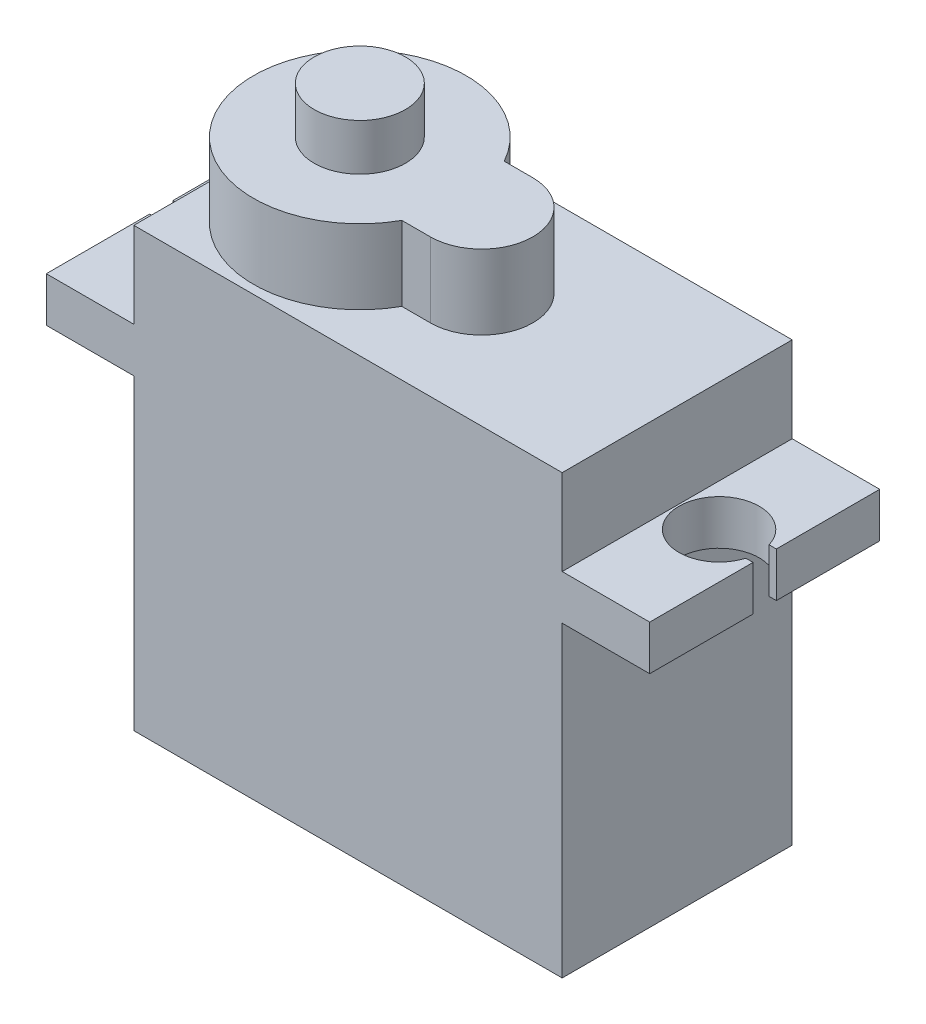
SolidWorks part; units mm, degrees
ref_plane "Front Plane" through (0, 0, 0) normal (0, 0, 1) x (1, 0, 0)
ref_plane "Top Plane" through (0, 0, 0) normal (0, 1, 0) x (1, 0, 0)
ref_plane "Right Plane" through (0, 0, 0) normal (1, 0, 0) x (0, 0, -1)
sketch "Sketch1" plane through (0, 0, 0) normal (0, 0, 1) x (1, 0, 0)
  line L0 (0, 0) -> (23, 0)
  line L1 (23, 0) -> (23, 16.5)
  line L2 (23, 16.5) -> (27.7, 16.5)
  line L3 (27.7, 16.5) -> (27.7, 18.9)
  line L4 (27.7, 18.9) -> (23, 18.9)
  line L5 (23, 18.9) -> (23, 23.5)
  line L6 (23, 23.5) -> (0, 23.5)
  line L7 (0, 23.5) -> (0, 18.9)
  line L8 (0, 18.9) -> (-4.7, 18.9)
  line L9 (-4.7, 18.9) -> (-4.7, 16.5)
  line L10 (-4.7, 16.5) -> (0, 16.5)
  line L11 (0, 16.5) -> (0, 0)
  dimension "D1" = 23
  dimension "D2" = 2.4
  dimension "D3" = 16.5
  dimension "D4" = 32.4
  dimension "D5" = 23.5
extrude "Boss-Extrude1" add sketch "Sketch1" along normal mid plane 12.35
sketch "Sketch3" plane through (0, 23.5, 0) normal (0, 1, 0) x (1, 0, 0)
  line L0 (12.5, 2.75) -> (10.9642, 2.75)
  line L1 (12.5, -2.75) -> (10.9642, -2.75)
  line L2 (0, -6.175) -> (0, 6.175) construction
  arc A0 (10.9642, 2.75) -> (10.9642, -2.75) centre (5.96, 0) ccw
  arc A1 (12.5, -2.75) -> (12.5, 2.75) centre (12.5, 0) ccw
  dimension "D2" = 5.71
  dimension "D1" = 5.5
  dimension "D3" = 6.54
  dimension "D4" = 12.5
extrude "Boss-Extrude2" add sketch "Sketch3" along normal blind 4
sketch "Sketch4" plane through (0, 27.5, 0) normal (0, 1, 0) x (1, 0, 0)
  circle A0 centre (5.96, 0) radius 2.45
  arc A1 (10.9642, 2.75) -> (10.9642, -2.75) centre (5.96, 0) ccw construction
  dimension "D1" = 4.9
extrude "Boss-Extrude3" add sketch "Sketch4" along normal blind 2.5
sketch "Sketch5" plane through (0, 18.9, 0) normal (0, 1, 0) x (1, 0, 0)
  line L0 (-4.7, 0.625) -> (-4.3113, 0.625)
  line L1 (-4.7, -6.175) -> (-4.7, 6.175) construction
  line L2 (-4.7, 0.625) -> (-4.7, -0.625)
  line L3 (-4.7, -0.625) -> (-4.3113, -0.625)
  line L4 (27.3113, 0.625) -> (27.7, 0.625)
  line L5 (27.7, -6.175) -> (27.7, 6.175) construction
  line L6 (27.7, 0.625) -> (27.7, -0.625)
  line L7 (27.7, -0.625) -> (27.3113, -0.625)
  arc A0 (27.3113, -0.625) -> (27.3113, 0.625) centre (25.25, 0) cw
  arc A1 (-4.3113, 0.625) -> (-4.3113, -0.625) centre (-2.25, 0) cw
  dimension "D3" = 2.154
  dimension "D1" = 1.25
  dimension "D2" = 1.25
  dimension "D4" = 27.5
extrude "Cut-Extrude1" cut sketch "Sketch5" against normal up to next
